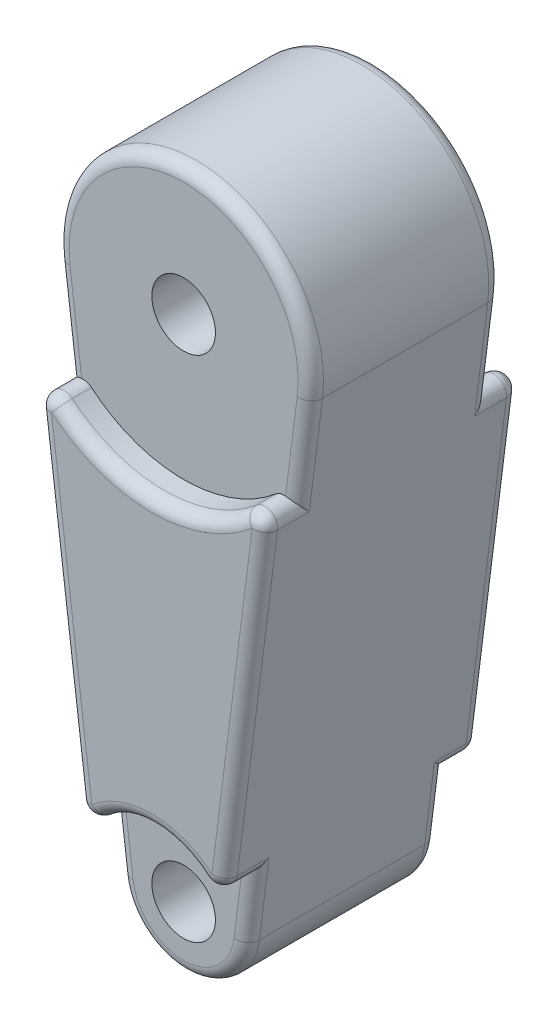
SolidWorks part; units mm, degrees
material "ABS"
ref_plane "Front Plane" through (0, 0, 0) normal (0, 0, 1) x (1, 0, 0)
ref_plane "Top Plane" through (0, 0, 0) normal (0, 1, 0) x (1, 0, 0)
ref_plane "Right Plane" through (0, 0, 0) normal (1, 0, 0) x (0, 0, -1)
sketch "Sketch1" plane through (0, 0, 0) normal (0, 0, 1) x (1, 0, 0)
  line L0 (-25.2008, 98.425) -> (-12.6004, -1.5875)
  line L2 (12.6004, -1.5875) -> (25.2008, 98.425)
  arc A0 (-25.2008, 98.425) -> (25.2008, 98.425) centre (0, 101.6) cw
  arc A1 (12.6004, -1.5875) -> (-12.6004, -1.5875) centre (0, 0) cw
  circle A2 centre (0, 0) radius 6.35
  circle A3 centre (0, 101.6) radius 6.35
  dimension "D1" = 12.7
  dimension "D2" = 25.4
  dimension "D4" = 12.7
  dimension "D3" = 101.6
extrude "Boss-Extrude1" add sketch "Sketch1" along normal blind 19.05
sketch "Sketch2" plane through (0, 0, 19.05) normal (0, 0, 1) x (1, 0, 0)
  line L0 (-13.791, 7.8628) -> (-23.5644, 85.4368)
  line L1 (-25.2008, 98.425) -> (-12.6004, -1.5875) construction
  line L2 (23.5644, 85.4368) -> (13.791, 7.8628)
  line L3 (12.6004, -1.5875) -> (25.2008, 98.425) construction
  circle A0 centre (0, 101.6) radius 28.575
  circle A1 centre (0, 0) radius 15.875
  line M3 (-25.2008, 98.425) -> (-12.6004, -1.5875)
  line M5 (12.6004, -1.5875) -> (25.2008, 98.425)
  dimension "D1" = 57.15
  dimension "D2" = 31.75
extrude "Boss-Extrude2" add sketch "Sketch2" along normal blind 6.35 contours A1 A0 M5 M3
fillet "Fillet1" radius 2.54 14 edges at (13.791, 7.8628, 22.225) (-13.791, 7.8628, 22.225) (-23.5644, 85.4368, 22.225) (23.5644, 85.4368, 22.225) (-13.1957, 3.1376, 19.05) (13.1957, 3.1376, 19.05) (24.3826, 91.9309, 19.05) (-24.3826, 91.9309, 19.05) (0, -12.7, 19.05) (0, 127, 19.05) (18.6777, 46.6498, 25.4) (-18.6777, 46.6498, 25.4) (0, 73.025, 25.4) (0, 15.875, 25.4)
mirror "Mirror4" about plane through (0, 101.6, 0) normal (0, 0, -1) of "Fillet1", "Boss-Extrude2", "Boss-Extrude1"
